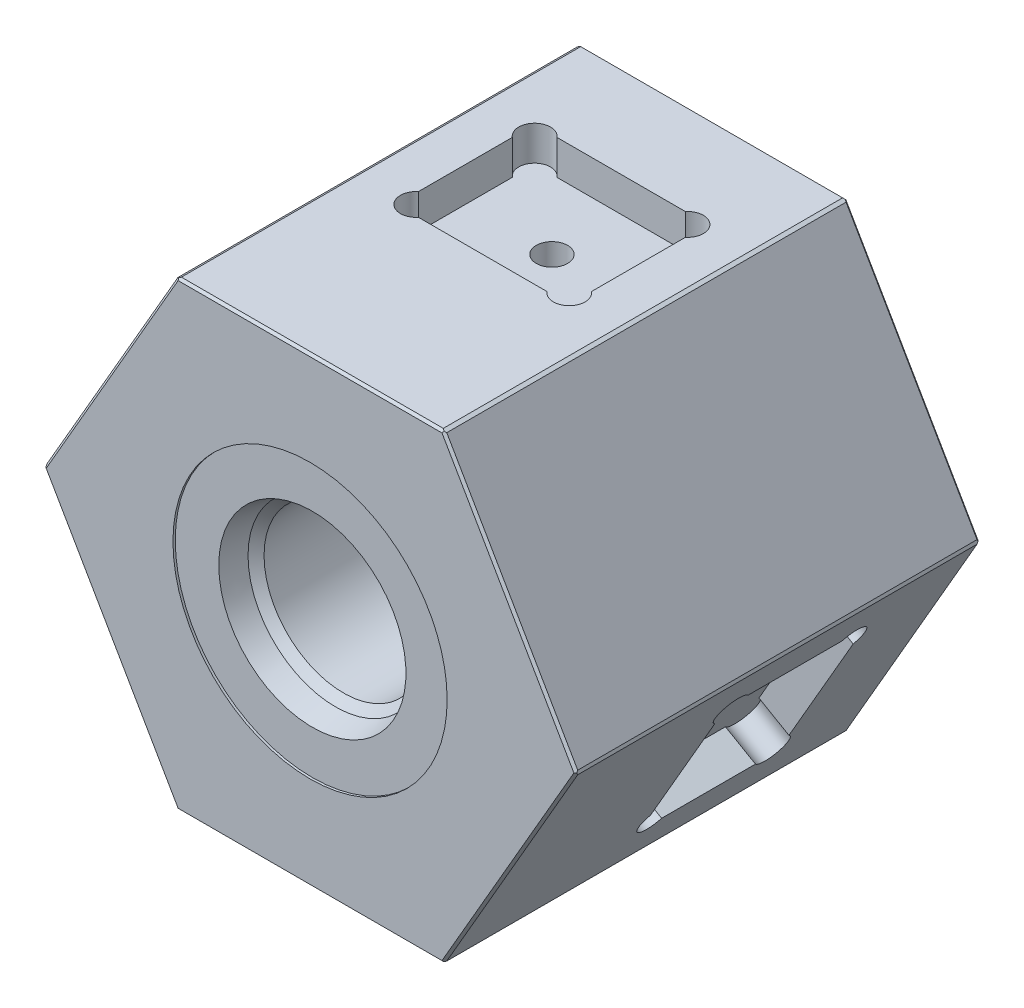
SolidWorks part; units mm, degrees
material "6061-T6 (SS)"
ref_plane "Front" through (0, 0, 0) normal (0, 0, 1) x (1, 0, 0)
ref_plane "Top" through (0, 0, 0) normal (0, 1, 0) x (1, 0, 0)
ref_plane "Right" through (0, 0, 0) normal (1, 0, 0) x (0, 0, -1)
sketch "Sketch1" plane through (0, 0, 0) normal (0, 0, 1) x (1, 0, 0)
  line L1 (29.3294, 0) -> (14.6647, 25.4)
  line L2 (14.6647, 25.4) -> (-14.6647, 25.4)
  line L3 (-14.6647, 25.4) -> (-29.3294, 0)
  line L4 (-29.3294, 0) -> (-14.6647, -25.4)
  line L5 (-14.6647, -25.4) -> (14.6647, -25.4)
  line L6 (14.6647, -25.4) -> (29.3294, 0)
  circle A0 centre (0, 0) radius 25.4 construction
  circle A1 centre (0, 0) radius 8.255
  dimension "D1" = 50.8
  dimension "D2" = 16.51
extrude "Boss-Extrude1" add sketch "Sketch1" along normal blind 44.45
sketch "Sketch2" plane through (0, 0, 44.45) normal (0, 0, 1) x (1, 0, 0)
  point P0 (0, 0)
ref_plane "Plane1" through (0, 0, 0) normal (0.866, 0.5, 0) x (0, 0, -1)
sketch "Sketch14" plane through (0, 25.4, 0) normal (0, 1, 0) x (1, 0, 0)
  line L0 (14.6647, 0) -> (-14.6647, -44.45) construction
  line L4 (14.6647, 0) -> (-14.6647, 0)
  line L5 (-14.6647, 0) -> (-14.6647, -44.45)
  line L6 (-14.6647, -44.45) -> (14.6647, -44.45)
  line L7 (14.6647, -44.45) -> (14.6647, 0)
  line L8 (14.6647, 0) -> (-14.6647, 0) construction
  line L9 (-14.6647, 0) -> (-14.6647, -44.45) construction
  line L10 (-14.6647, -44.45) -> (14.6647, -44.45) construction
  line L11 (14.6647, -44.45) -> (14.6647, 0) construction
  circle A0 centre (0, -22.225) radius 2.4638
  dimension "D1" = 0
sketch "Sketch21" plane through (0, 0, 44.45) normal (0, 0, 1) x (1, 0, 0)
  line L0 (-29.3294, 0) -> (-24.2494, 0) construction
  line L1 (-24.2494, 8.7988) -> (-24.2494, -8.7988)
  line L3 (-24.2494, -8.7988) -> (-41.847, -8.7988)
  line L4 (-24.2494, -8.7988) -> (-24.2494, 8.7988)
  line L5 (-24.2494, 8.7988) -> (-41.847, 8.7988)
  line L6 (14.6647, -25.4) -> (29.3294, 0)
  line L7 (29.3294, 0) -> (14.6647, 25.4)
  line L8 (14.6647, 25.4) -> (-14.6647, 25.4)
  line L9 (-14.6647, 25.4) -> (-29.3294, 0)
  line L10 (-29.3294, 0) -> (-14.6647, -25.4)
  line L11 (-14.6647, -25.4) -> (14.6647, -25.4)
  line L12 (14.6647, -25.4) -> (29.3294, 0) construction
  line L13 (29.3294, 0) -> (14.6647, 25.4) construction
  line L14 (14.6647, 25.4) -> (-14.6647, 25.4) construction
  line L15 (-14.6647, 25.4) -> (-29.3294, 0) construction
  line L16 (-29.3294, 0) -> (-14.6647, -25.4) construction
  line L17 (-14.6647, -25.4) -> (14.6647, -25.4) construction
  line L18 (-41.847, -8.7988) -> (-41.847, 8.7988)
  point P10 (-24.2494, 0)
  dimension "D2" = 5.08
  dimension "D1" = 0
sketch "Sketch22" plane through (0, 0, 0) normal (0, 0, -1) x (-1, 0, 0)
  circle A0 centre (0, 0) radius 6.9977
  circle A1 centre (0, 0) radius 9.2075
  circle A2 centre (0, 0) radius 10.9728
  dimension "D1" = 13.9954
  dimension "D2" = 18.415
  dimension "D3" = 21.9456
sketch "Sketch23" plane through (0, 0, 0) normal (0, 0, -1) x (-1, 0, 0)
  line L0 (0, 0) -> (0, 12.192) construction
  point P4 (0, 12.192)
sketch "Sketch48" plane through (0, 0, 0) normal (0, 0, -1) x (-1, 0, 0)
  line L0 (15.875, 0) -> (13.0175, 0) construction
  circle A0 centre (0, 0) radius 13.0175
  circle A1 centre (0, 0) radius 18.7325
  dimension "D1" = 26.035
  dimension "D3" = 37.465
  dimension "D2" = 2.8575
sketch "Sketch32" plane through (-21.997, -12.7, 0) normal (-0.866, -0.5, 0) x (0, 0, 1)
  line L0 (0, 14.6647) -> (44.45, -14.6647) construction
  line L2 (8.0518, -6.35) -> (36.3982, -6.35)
  line L3 (8.0518, -6.35) -> (8.0518, 6.35)
  line L4 (0, 14.6647) -> (0, -14.6647)
  line L5 (0, -14.6647) -> (44.45, -14.6647)
  line L6 (44.45, -14.6647) -> (44.45, 14.6647)
  line L7 (44.45, 14.6647) -> (0, 14.6647)
  line L8 (0, 14.6647) -> (0, -14.6647) construction
  line L9 (0, -14.6647) -> (44.45, -14.6647) construction
  line L10 (44.45, -14.6647) -> (44.45, 14.6647) construction
  line L11 (44.45, 14.6647) -> (0, 14.6647) construction
  line L12 (8.0518, 6.35) -> (36.3982, 6.35)
  line L13 (36.3982, -6.35) -> (36.3982, 6.35)
  line L14 (8.0518, -6.35) -> (36.3982, 6.35) construction
  line L15 (8.0518, 6.35) -> (36.3982, -6.35) construction
  point P2 (22.225, 0)
  point P4 (22.225, 0)
  dimension "D1" = 0
extrude "Cut-Extrude12" [suppressed] cut sketch "Sketch32" against normal blind 7.62
sketch "Sketch33" [suppressed] plane through (-21.997, -12.7, 0) normal (-0.866, -0.5, 0) x (0, 0, 1)
  line L0 (8.0518, 6.35) -> (8.2763, 6.1255) construction
  line L1 (22.225, 6.35) -> (22.225, 3.261) construction
  line L2 (8.0518, 0) -> (11.2132, 0) construction
  line L4 (0, 14.6647) -> (0, -14.6647)
  line L5 (0, -14.6647) -> (44.45, -14.6647)
  line L6 (44.45, -14.6647) -> (44.45, 14.6647)
  line L7 (44.45, 14.6647) -> (0, 14.6647)
  line L8 (0, 14.6647) -> (0, -14.6647) construction
  line L9 (0, -14.6647) -> (44.45, -14.6647) construction
  line L10 (44.45, -14.6647) -> (44.45, 14.6647) construction
  line L11 (44.45, 14.6647) -> (0, 14.6647) construction
  line L12 (36.3982, -6.35) -> (36.3982, 6.35)
  line L13 (36.3982, 6.35) -> (8.0518, 6.35)
  line L14 (8.0518, 6.35) -> (8.0518, -6.35)
  line L15 (8.0518, -6.35) -> (36.3982, -6.35)
  line L16 (36.3982, -6.35) -> (36.3982, 6.35) construction
  line L17 (36.3982, 6.35) -> (8.0518, 6.35) construction
  line L18 (8.0518, 6.35) -> (8.0518, -6.35) construction
  line L19 (8.0518, -6.35) -> (36.3982, -6.35) construction
  circle A0 centre (8.2763, 6.1255) radius 1.5875
  circle A1 centre (8.2763, -6.1255) radius 1.5875
  circle A2 centre (36.1737, -6.1255) radius 1.5875
  circle A3 centre (36.1737, 6.1255) radius 1.5875
  dimension "D3" = 3.175
  dimension "D4" = 0.3175
extrude "Cut-Extrude13" [suppressed] cut sketch "Sketch33" against normal blind 7.62
pattern_circular "CirPattern2" [suppressed] count 3 over 360
chamfer "Chamfer1" distance 0.254 angle 45 6 edges at (0, -25.4, 44.45) (-21.997, -12.7, 44.45) (-21.997, 12.7, 44.45) (0, 25.4, 44.45) (21.997, -12.7, 44.45) (21.997, 12.7, 44.45)
chamfer "Chamfer2" distance 0.254 angle 45 6 edges at (0, 25.4, 0) (-21.997, 12.7, 0) (-21.997, -12.7, 0) (0, -25.4, 0) (21.997, -12.7, 0) (21.997, 12.7, 0)
sketch "Sketch31" plane through (0, 0, 0) normal (0, 0, -1) x (-1, 0, 0)
  line L0 (24.2494, 8.7988) -> (24.2494, -8.7988) construction
  line L1 (24.2494, -8.7988) -> (41.847, -8.7988) construction
  line L2 (41.847, -8.7988) -> (41.847, 8.7988) construction
  line L3 (24.2494, 8.7988) -> (41.847, 8.7988) construction
  line L4 (24.2494, -8.7988) -> (24.2494, 8.7988) construction
  line L5 (24.2494, 8.7988) -> (24.2494, -8.7988) construction
  line L6 (24.2494, -8.7988) -> (41.847, -8.7988)
  line L7 (41.847, -8.7988) -> (41.847, 8.7988)
  line L8 (24.2494, 8.7988) -> (41.847, 8.7988)
  line L9 (24.2494, -8.7988) -> (24.2494, 8.7988)
sketch "Sketch26" plane through (-21.997, 12.7, 0) normal (-0.866, 0.5, 0) x (0, 0, 1)
  line L0 (0, 14.6647) -> (44.45, -1.9647) construction
  line L2 (8.0518, 0) -> (36.3982, 0)
  line L3 (8.0518, 0) -> (8.0518, 12.7)
  line L4 (0.254, 14.6647) -> (0.254, -14.6647)
  line L12 (8.0518, 12.7) -> (36.3982, 12.7)
  line L13 (36.3982, 0) -> (36.3982, 12.7)
  line L14 (8.0518, 0) -> (36.3982, 12.7) construction
  line L15 (8.0518, 12.7) -> (36.3982, 0) construction
  line L18 (44.196, 14.6647) -> (0.254, 14.6647)
  line L19 (44.196, 14.6647) -> (0.254, 14.6647)
  line L20 (0.254, -14.6647) -> (44.196, -14.6647)
  line L21 (0.254, -14.6647) -> (44.196, -14.6647)
  line L30 (44.196, -14.6647) -> (44.196, 14.6647)
  line L33 (0.254, 14.6647) -> (0.254, -14.6647)
  line L34 (44.196, -14.6647) -> (44.196, 14.6647)
  point P2 (22.225, 6.35)
  point P4 (22.225, 6.35)
  dimension "D2" = 28.3464
  dimension "D3" = 12.7
  dimension "D1" = 0
sketch "Sketch41" plane through (21.997, 12.7, 0) normal (0.866, 0.5, 0) x (0, 0, -1)
  line L0 (-44.196, 14.6647) -> (-0.254, -14.6647) construction
  line L2 (-27.305, 11.176) -> (-17.145, 11.176)
  line L3 (-31.115, 7.366) -> (-31.115, -7.366)
  line L4 (-0.254, -14.6647) -> (-0.254, 14.6647)
  line L5 (-44.196, -14.6647) -> (-0.254, -14.6647)
  line L7 (-44.196, -14.6647) -> (-0.254, -14.6647)
  line L12 (-27.305, -11.176) -> (-17.145, -11.176)
  line L13 (-13.335, 7.366) -> (-13.335, -7.366)
  line L14 (-31.115, 11.176) -> (-13.335, -11.176) construction
  line L15 (-31.115, -11.176) -> (-13.335, 11.176) construction
  line L19 (-0.254, 14.6647) -> (-44.196, 14.6647)
  line L20 (-0.254, 14.6647) -> (-44.196, 14.6647)
  line L23 (-44.196, 14.6647) -> (-44.196, -14.6647)
  line L27 (-0.254, -14.6647) -> (-0.254, 14.6647)
  line L28 (-44.196, 14.6647) -> (-44.196, -14.6647)
  arc A0 (-27.305, -11.176) -> (-31.115, -7.366) centre (-27.305, -7.366) cw
  arc A1 (-13.335, -7.366) -> (-17.145, -11.176) centre (-17.145, -7.366) cw
  arc A2 (-17.145, 11.176) -> (-13.335, 7.366) centre (-17.145, 7.366) cw
  arc A3 (-27.305, 11.176) -> (-31.115, 7.366) centre (-27.305, 7.366) ccw
  point P2 (-22.225, 0)
  dimension "D2" = 3.81
  dimension "D1" = 0
sketch "Sketch42" plane through (0, 25.4, 0) normal (0, 1, 0) x (1, 0, 0)
  line L0 (-14.6647, -0.254) -> (14.6647, -44.196) construction
  line L1 (-14.6647, -44.196) -> (14.6647, -0.254) construction
  line L2 (-7.62, -10.2108) -> (7.62, -10.2108)
  line L3 (-9.525, -12.1158) -> (-9.525, -23.5458)
  line L4 (14.6647, -0.254) -> (-14.6647, -0.254)
  line L5 (14.6647, -44.196) -> (14.6647, -0.254)
  line L7 (14.6647, -44.196) -> (14.6647, -0.254)
  line L12 (-7.62, -25.4508) -> (7.62, -25.4508)
  line L13 (9.525, -12.1158) -> (9.525, -23.5458)
  line L14 (-9.525, -10.2108) -> (9.525, -25.4508) construction
  line L15 (-9.525, -25.4508) -> (9.525, -10.2108) construction
  line L16 (0, -22.225) -> (0, -17.8308) construction
  line L19 (-14.6647, -0.254) -> (-14.6647, -44.196)
  line L20 (-14.6647, -0.254) -> (-14.6647, -44.196)
  line L23 (-14.6647, -44.196) -> (14.6647, -44.196)
  line L27 (14.6647, -0.254) -> (-14.6647, -0.254)
  line L28 (-14.6647, -44.196) -> (14.6647, -44.196)
  arc A0 (-7.62, -25.4508) -> (-9.525, -23.5458) centre (-7.62, -23.5458) cw
  arc A1 (9.525, -23.5458) -> (7.62, -25.4508) centre (7.62, -23.5458) cw
  arc A2 (7.62, -10.2108) -> (9.525, -12.1158) centre (7.62, -12.1158) cw
  arc A3 (-7.62, -10.2108) -> (-9.525, -12.1158) centre (-7.62, -12.1158) ccw
  point P2 (0, -17.8308)
  dimension "D2" = 1.905
  dimension "D3" = 15.24
  dimension "D4" = 19.05
  dimension "D5" = 43.942
  dimension "D6" = 17.5768
extrude "Cut-Extrude16" cut sketch "Sketch42" against normal blind 3.81 contours A3 L2 A2 L13 A1 L12 A0 L3
sketch "Sketch43" plane through (0, 0, 0) normal (0, 1, 0) x (1, 0, 0)
  line L0 (0, -44.45) -> (0, -50044.45) construction
  line L1 (-8.255, -44.45) -> (8.255, -44.45) construction
  line L3 (14.518, -44.45) -> (-14.518, -44.45) construction
  line L4 (10.2997, -44.196) -> (10.2997, -41.656) construction
  line L5 (10.2997, -44.196) -> (9.6191, -41.656)
  line L6 (10.2997, -41.656) -> (11.3639, -41.656) construction
  line L7 (0, -50.7062) -> (8.7376, -50.7062) construction
  line L8 (9.6191, -41.656) -> (8.7376, -40.7745)
  line L9 (8.7376, -50.7062) -> (8.7376, -51.9414) construction
  line L10 (8.7376, -40.7745) -> (8.7376, -23.2993)
  line L13 (8.7376, -23.2993) -> (4.9657, -21.1216)
  line L14 (0, -59.4121) -> (4.9657, -59.4121) construction
  line L15 (4.9657, -59.4121) -> (4.9657, 16.661) construction
  line L16 (4.9657, -21.1216) -> (0, -21.1216)
  line L19 (10.2997, -44.196) -> (15.0876, -44.196)
  line L20 (0, -44.45) -> (0, -21.1216)
  line L21 (15.0876, -44.196) -> (15.0876, -44.45)
  line L22 (15.0876, -44.45) -> (0, -44.45)
  line L24 (14.518, -44.45) -> (-14.518, -44.45) construction
  point P4 (0, -44.45)
  dimension "D1" = 15
  dimension "D2" = 0.8815
  dimension "D3" = 2.54
  dimension "D4" = 45
  dimension "D5" = 8.7376
  dimension "D6" = 4.9657
  dimension "D7" = 60
  dimension "D8" = 17.4752
  dimension "D9" = 0.254
  dimension "D10" = 15.0876
  dimension "D11" = 4.9657
  dimension "D12" = 23.3284
revolve "Cut-Revolve1" cut sketch "Sketch43" angle 360 about L0
pattern_circular "CirPattern3" count 3 over 360 about axis through (0, 0, 0) along (0, 0, 1) of "Cut-Extrude16"
ref_plane "YEAH BOIIIII" through (0, 0, 12.7) normal (0, 0, 1) x (1, 0, 0)
sketch "Sketch44" plane through (0, 0, 12.7) normal (0, 0, 1) x (1, 0, 0)
  line L0 (-21.997, 12.7) -> (43279.2731, -24987.3) construction
  line L1 (-14.6647, 25.4) -> (-29.3294, 0) construction
  line L2 (-21.764, 12.5655) -> (-24.8565, 7.2092) construction
  line L3 (-24.8565, 7.2092) -> (-22.8108, 6.0281) construction
  line L4 (-24.8565, 7.2092) -> (-22.5597, 6.4629)
  line L5 (-9.465, 2.9423) -> (-2.8658, -0.8677)
  line L6 (-22.8108, 6.0281) -> (-23.9458, 4.0621) construction
  line L7 (-26.3057, 15.1876) -> (-28.7568, 10.9421) construction
  line L8 (-28.7568, 10.9421) -> (-27.2096, 10.0489) construction
  line L9 (-22.5597, 6.4629) -> (-21.4934, 6.7486)
  line L10 (-21.4934, 6.7486) -> (-12.1828, 1.3731)
  line L11 (-12.1828, 1.3731) -> (-9.465, 2.9423)
  line L12 (-23.5705, 13.6084) -> (-24.6627, 11.7167) construction
  line L13 (-24.6627, 11.7167) -> (-23.5031, 11.0472) construction
  line L14 (-2.8658, -0.8677) -> (-1.7736, 1.024)
  line L15 (-1.7736, 1.024) -> (-21.764, 12.5655)
  line L16 (-24.8565, 7.2092) -> (-27.0218, 3.4587)
  line L17 (-27.0218, 3.4587) -> (-27.2548, 3.5932)
  line L18 (-27.2548, 3.5932) -> (-21.997, 12.7)
  line L19 (-21.997, 12.7) -> (-21.764, 12.5655)
  line L20 (-14.6647, 25.4) -> (-29.3294, 0) construction
  line L21 (-14.6647, 25.4) -> (-29.3294, 0) construction
  point P4 (-21.997, 12.7)
  dimension "D1" = 6.1849
  dimension "D2" = 2.3622
  dimension "D3" = 12
  dimension "D4" = 4.9022
  dimension "D5" = 45
  dimension "D6" = 13.8938
  dimension "D7" = 60
  dimension "D8" = 2.1844
  dimension "D9" = 23.0829
  dimension "D10" = 10.5156
  dimension "D11" = 0.2691
  dimension "D12" = 2.1844
revolve "Cut-Revolve2" cut sketch "Sketch44" angle 360 about L15
pattern_circular "CirPattern4" count 2 over 120 about axis through (0, 0, 0) along (0, 0, 1) of "Cut-Revolve2"
sketch "Sketch45" plane through (-18.6975, -10.795, 0) normal (-0.866, -0.5, 0) x (0, 0, 1)
  line L0 (17.8308, -9.525) -> (17.8308, 9.525) construction
  line L1 (12.1158, -9.525) -> (23.5458, -9.525) construction
  line L2 (12.1158, 9.525) -> (23.5458, 9.525) construction
  line L3 (10.2108, 0) -> (25.4508, 0) construction
  line L4 (10.2108, -7.62) -> (10.2108, 7.62) construction
  line L5 (25.4508, -7.62) -> (25.4508, 7.62) construction
  point P12 (17.8308, 0)
hole_wizard "#8-32 Tapped Hole1" positions "Sketch46" profile "Sketch47" tap size "#8-32" standard "ANSI Inch"
sketch "Sketch46" plane through (-18.6975, -10.795, 0) normal (-0.866, -0.5, 0) x (0, 0, 1)
  point P0 (17.8308, 0)
sketch "Sketch47" plane through (-18.6975, -10.795, 17.8308) normal (0, 0, 1) x (0.5, -0.866, 0)
  line L0 (0, 0) -> (0, 11.1978)
  line L1 (0, 11.1978) -> (1.7272, 10.16)
  line L2 (1.7272, 10.16) -> (1.7272, 0)
  line L5 (1.7272, 0) -> (0, 0)
  line L10 (0, 11.1978) -> (-1.7272, 10.16) construction
  line L11 (0, -6.35) -> (0, 107.95) construction
  dimension "Tap Drill Dia." = 3.4544
  dimension "Tap Drill Depth" = 10.16
  dimension "Drill Angle" = 118
cosmetic thread "Hole Thread2" parameters "D1"=9.398, "D2"=4.1656
pattern_circular "CirPattern5" count 3 over 360 about axis through (0, 0, 0) along (0, 0, 1) of "#8-32 Tapped Hole1"
sketch "Sketch49" plane through (0, 0, 0) normal (1, 0, 0) x (0, 0, -1)
  line L0 (0, 0) -> (50000, 0) construction
  line L1 (0, 0) -> (0, 23.622)
  line L2 (0, 0) -> (0, 25.146) construction
  line L3 (0, 23.622) -> (0.381, 23.622)
  line L4 (0.381, 23.622) -> (0.381, 15.8432)
  line L5 (0.381, 15.8432) -> (2.667, 15.8432)
  line L6 (2.667, 15.8432) -> (2.667, 14.605)
  line L7 (2.667, 14.605) -> (5.842, 14.605)
  line L8 (0, -8.255) -> (0, 8.255) construction
  line L9 (0, -8.255) -> (0, 8.255) construction
  line L10 (0, 8.255) -> (-2.4758, 8.255) construction
  line L11 (5.842, 14.605) -> (5.842, 12.7508)
  line L12 (5.842, 8.255) -> (0, 8.255)
  line L13 (0, 8.255) -> (0, 23.622)
  line L14 (14.8885, 0) -> (14.8885, 12.7508) construction
  line L15 (5.842, 12.7508) -> (4.5466, 12.7508)
  line L16 (4.5466, 12.7508) -> (4.5466, 10.6172)
  line L17 (4.5466, 10.6172) -> (5.842, 10.6172)
  line L18 (5.842, 10.6172) -> (5.842, 8.255)
  dimension "D1" = 23.622
  dimension "D2" = 15.8432
  dimension "D3" = 14.605
  dimension "D4" = 3.175
  dimension "D5" = 2.286
  dimension "D6" = 12.7508
  dimension "D7" = 1.2954
  dimension "D8" = 2.1336
  dimension "D9" = 0.381
  dimension "D10" = 5.461
revolve "Revolve1" add sketch "Sketch49" angle 360 about L0
hole_wizard "#6-32 Tapped Hole1" positions "Sketch24" profile "Sketch25" tap size "#6-32" standard "ANSI Inch"
sketch "Sketch24" plane through (0, 0, -0.381) normal (0, 0, -1) x (-1, 0, 0)
  line L0 (0, 0) -> (20.32, 0) construction
  line L1 (0, 0) -> (24.8294, -14.3353) construction
  line L11 (14.518, -25.146) -> (14.6647, -25.4)
  line L12 (14.6647, -25.4) -> (29.3294, 0)
  line L13 (29.3294, 0) -> (29.0361, 0)
  line L14 (29.0361, 0) -> (14.518, -25.146)
  line L15 (14.518, -25.146) -> (14.6647, -25.4)
  line L16 (14.6647, -25.4) -> (29.3294, 0)
  line L17 (29.3294, 0) -> (29.0361, 0)
  line L18 (29.0361, 0) -> (14.518, -25.146) construction
  point P11 (20.32, 0)
  dimension "D1" = 20.32
  dimension "D2" = 0
  dimension "D3" = 30
sketch "Sketch25" plane through (-20.32, 0, -0.381) normal (1, 0, 0) x (0, 1, 0)
  line L0 (0, 0) -> (0, 7.1627)
  line L1 (0, 7.1627) -> (1.3525, 6.35)
  line L2 (1.3525, 6.35) -> (1.3525, 0)
  line L5 (1.3525, 0) -> (0, 0)
  line L10 (0, 7.1627) -> (-1.3526, 6.35) construction
  line L11 (0, -6.35) -> (0, 107.95) construction
  dimension "Tap Drill Dia." = 2.7051
  dimension "Tap Drill Depth" = 6.35
  dimension "Drill Angle" = 118
cosmetic thread "Hole Thread11" parameters "D1"=5.588, "D2"=3.5052
pattern_circular "CirPattern6" count 2 over 60 about axis through (0, 0, -5.842) along (0, 0, 1) of "#6-32 Tapped Hole1"
pattern_circular "CirPattern7" count 2 over 360 about axis through (0, 0, 0) along (0, 0, 1) of "CirPattern6", "#6-32 Tapped Hole1"
sketch "Sketch51" plane through (0, 0, -0.381) normal (0, 0, -1) x (-1, 0, 0)
  line L0 (0, 0) -> (25.1717, -14.5329) construction
  line L1 (14.518, -25.146) -> (29.0361, 0) construction
  line L2 (14.518, -25.146) -> (29.0361, 0) construction
  line L3 (0, 0) -> (-3.5285, -20.0113) construction
  line L4 (0, 0) -> (-15.566, -13.0614) construction
  line L5 (0, 0) -> (10.16, -17.5976) construction
  line L6 (0, 0) -> (3.5285, 20.0113) construction
  line L7 (0, 0) -> (15.566, 13.0614) construction
  line L8 (0, 0) -> (20.32, 0) construction
  dimension "D3" = 20.32
  dimension "D4" = 20.32
  dimension "D5" = 30
  dimension "D1" = 40
  dimension "D2" = 40
  dimension "D6" = 30
hole_wizard "#6-32 Tapped Hole2" positions "Sketch56" profile "Sketch57" tap size "#6-32" standard "ANSI Inch"
sketch "Sketch56" plane through (0, 0, -0.381) normal (0, 0, -1) x (-1, 0, 0)
  point P0 (15.566, 13.0614)
  point P3 (3.5285, 20.0113)
  point P6 (-15.566, -13.0614)
  point P9 (-3.5285, -20.0113)
sketch "Sketch57" plane through (-15.566, 13.0614, -0.381) normal (1, 0, 0) x (0, 1, 0)
  line L0 (0, 0) -> (0, 7.1627)
  line L1 (0, 7.1627) -> (1.3525, 6.35)
  line L2 (1.3525, 6.35) -> (1.3525, 0)
  line L5 (1.3525, 0) -> (0, 0)
  line L10 (0, 7.1627) -> (-1.3526, 6.35) construction
  line L11 (0, -6.35) -> (0, 107.95) construction
  dimension "Tap Drill Dia." = 2.7051
  dimension "Tap Drill Depth" = 6.35
  dimension "Drill Angle" = 118
cosmetic thread "Hole Thread6" parameters "D1"=5.588, "D2"=3.5052
cosmetic thread "Hole Thread7" parameters "D1"=5.588, "D2"=3.5052
cosmetic thread "Hole Thread8" parameters "D1"=5.588, "D2"=3.5052
cosmetic thread "Hole Thread9" parameters "D1"=5.588, "D2"=3.5052
sketch "Sketch50" plane through (0, 0, -0.381) normal (0, 0, -1) x (-1, 0, 0)
  line L0 (16.8026, -11.537) -> (18.3927, -8.783) construction
  line L2 (0, 0) -> (17.5976, -10.16) construction
  line L3 (17.5976, -10.16) -> (17.2039, -10.8419) construction
  line L4 (17.5976, -10.16) -> (17.9913, -9.4781) construction
  line L5 (17.2039, -10.8419) -> (17.9913, -9.4781) construction
  line L6 (16.5088, -10.4406) -> (17.2962, -9.0768)
  line L7 (17.899, -11.2432) -> (18.6864, -9.8794)
  line L8 (0, 0) -> (-17.5976, 10.16) construction
  line L9 (0, 0) -> (17.5976, -10.16) construction
  line L10 (0, 0) -> (25.1717, -14.5329) construction
  line L11 (0, 0) -> (-14.6647, -25.4) construction
  circle A0 centre (0, 0) radius 20.32 construction
  arc A1 (16.5088, -10.4406) -> (17.899, -11.2432) centre (17.2039, -10.8419) ccw
  arc A2 (18.6864, -9.8794) -> (17.2962, -9.0768) centre (17.9913, -9.4781) ccw
  point P5 (17.5976, -10.16)
  point P9 (17.5976, -10.16)
  point P16 (0, 0)
  dimension "D5" = 0.8026
  dimension "D6" = 40.64
  dimension "D3" = 0.7874
  dimension "D4" = 0.7874
  dimension "D2" = 180
extrude "Boss-Extrude2" add sketch "Sketch50" along normal blind 1.27
sketch "Sketch58" plane through (0, 0, -5.842) normal (0, 0, -1) x (-1, 0, 0)
  circle A0 centre (0, 0) radius 10.6172 construction
  circle A1 centre (0, 0) radius 12.7508 construction
  circle A2 centre (0, 0) radius 10.6172
  circle A3 centre (0, 0) radius 12.7508
chamfer "Chamfer3" distance 0.254 angle 30 6 edges at (14.6647, -25.4, 22.225) (29.3294, 0, 22.225) (14.6647, 25.4, 22.225) (-14.6647, -25.4, 22.225) (-14.6647, 25.4, 22.225) (-29.3294, 0, 22.225)
sketch "Sketch60" plane through (0, 25.4, 0) normal (0, 1, 0) x (1, 0, 0)
  line L0 (-7.62, -10.2108) -> (-9.525, -10.2108) construction
  line L1 (-9.525, -10.2108) -> (-9.525, -12.1158) construction
  line L2 (-9.525, -10.2108) -> (-8.4137, -11.3221) construction
  line L4 (14.6647, -44.196) -> (14.6647, -0.254)
  line L5 (14.6647, -0.254) -> (-14.6647, -0.254)
  line L6 (-14.6647, -0.254) -> (-14.6647, -44.196)
  line L7 (-14.6647, -44.196) -> (14.6647, -44.196)
  line L8 (14.6647, -44.196) -> (14.6647, -0.254)
  line L9 (14.6647, -0.254) -> (-14.6647, -0.254)
  line L10 (-14.6647, -0.254) -> (-14.6647, -44.196)
  line L11 (-14.6647, -44.196) -> (14.6647, -44.196)
  line L12 (7.62, -10.2108) -> (-7.62, -10.2108)
  line L13 (9.525, -23.5458) -> (9.525, -12.1158)
  line L14 (-7.62, -25.4508) -> (7.62, -25.4508)
  line L15 (-9.525, -12.1158) -> (-9.525, -23.5458)
  line L16 (7.62, -10.2108) -> (-7.62, -10.2108) construction
  line L17 (9.525, -23.5458) -> (9.525, -12.1158) construction
  line L18 (-7.62, -25.4508) -> (7.62, -25.4508) construction
  line L19 (-9.525, -12.1158) -> (-9.525, -23.5458) construction
  circle A1 centre (-8.4137, -11.3221) radius 1.7462
  arc A4 (9.525, -12.1158) -> (7.62, -10.2108) centre (7.62, -12.1158) ccw
  arc A5 (7.62, -25.4508) -> (9.525, -23.5458) centre (7.62, -23.5458) ccw
  arc A6 (-9.525, -23.5458) -> (-7.62, -25.4508) centre (-7.62, -23.5458) ccw
  arc A7 (-7.62, -10.2108) -> (-9.525, -12.1158) centre (-7.62, -12.1158) ccw
  arc A8 (9.525, -12.1158) -> (7.62, -10.2108) centre (7.62, -12.1158) ccw construction
  arc A9 (7.62, -25.4508) -> (9.525, -23.5458) centre (7.62, -23.5458) ccw construction
  arc A10 (-9.525, -23.5458) -> (-7.62, -25.4508) centre (-7.62, -23.5458) ccw construction
  arc A11 (-7.62, -10.2108) -> (-9.525, -12.1158) centre (-7.62, -12.1158) ccw construction
  dimension "D4" = 3.4925
  dimension "D3" = 1.5716
extrude "Cut-Extrude17" cut sketch "Sketch60" against normal up to surface (3.81 mm away) contours A1 up to face at (0, 21.59, 19.558)
ref_plane "Plane2" through (0, 0, 0) normal (1, 0, 0) x (0, 0, -1)
ref_plane "Plane3" through (0, 0, 17.8308) normal (0, 0, 1) x (1, 0, 0)
mirror "Mirror1" about plane through (0, 0, 0) normal (1, 0, 0) of "Cut-Extrude17"
mirror "Mirror2" about plane through (0, 0, 17.8308) normal (0, 0, 1) of "Mirror1", "Cut-Extrude17"
sketch "Sketch61" plane through (-21.997, -12.7, 0) normal (-0.866, -0.5, 0) x (0, 0, 1)
  line L0 (25.4508, -7.62) -> (25.4508, 7.62) construction
  line L1 (12.1158, 9.525) -> (23.5458, 9.525) construction
  line L2 (25.4508, -7.62) -> (25.4508, 7.62) construction
  line L3 (12.1158, 9.525) -> (23.5458, 9.525) construction
  line L4 (23.5458, 9.525) -> (25.4508, 9.525) construction
  line L5 (25.4508, 9.525) -> (25.4508, 7.62) construction
  line L6 (25.4508, 9.525) -> (24.3395, 8.4137) construction
  circle A0 centre (24.3395, 8.4137) radius 1.7462
  dimension "D1" = 3.4925
  dimension "D2" = 1.5716
extrude "Cut-Extrude18" cut sketch "Sketch61" against normal up to surface (3.81 mm away) up to face at (-17.8339, -12.2908, 17.8308)
ref_plane "Plane4" through (0, 0, 17.8308) normal (0, 0, -1) x (-1, 0, 0)
ref_plane "Plane5" through (0, 0, 0) normal (0.5, -0.866, 0) x (-0.866, -0.5, 0)
mirror "Mirror3" about plane through (0, 0, 0) normal (0.5, -0.866, 0) of "Cut-Extrude18"
mirror "Mirror4" about plane through (0, 0, 17.8308) normal (0, 0, -1) of "Cut-Extrude18", "Mirror3"
ref_plane "Plane6" through (0, 0, 17.8308) normal (0, 0, -1) x (-1, 0, 0)
ref_plane "Plane7" through (0, 0, 0) normal (0.5, 0.866, 0) x (0.866, -0.5, 0)
sketch "Sketch62" plane through (21.997, -12.7, 0) normal (0.866, -0.5, 0) x (0, 0, -1)
  line L0 (-12.1158, -9.525) -> (-23.5458, -9.525) construction
  line L1 (-25.4508, 7.62) -> (-25.4508, -7.62) construction
  line L2 (-12.1158, -9.525) -> (-23.5458, -9.525) construction
  line L3 (-25.4508, 7.62) -> (-25.4508, -7.62) construction
  line L4 (-25.4508, -7.62) -> (-25.4508, -9.525) construction
  line L5 (-25.4508, -9.525) -> (-23.5458, -9.525) construction
  line L6 (-25.4508, -9.525) -> (-24.3395, -8.4137) construction
  circle A0 centre (-24.3395, -8.4137) radius 1.7462
  dimension "D2" = 3.4925
  dimension "D1" = 1.5716
extrude "Cut-Extrude19" cut sketch "Sketch62" against normal up to surface (3.81 mm away) contours A0 up to face at (19.5611, -9.2992, 17.8308)
mirror "Mirror5" about plane through (0, 0, 0) normal (0.5, 0.866, 0) of "Cut-Extrude19"
mirror "Mirror6" about plane through (0, 0, 17.8308) normal (0, 0, -1) of "Cut-Extrude19", "Mirror5"
equation "\"D4@Sketch33\"=0.1*\"D3@Sketch33\""
equation "\"D4@Sketch42\"=1.25*\"D3@Sketch42\""
equation "\"D3@Sketch48\"=\"D1@Sketch48\"+(4*\"D2@Sketch48\")"
equation "\"D6@Sketch42\"=\"D5@Sketch42\"*.4"
equation "\"D4@Sketch50\"=\"D3@Sketch50\""
equation "\"D4@Sketch51\"=\"D3@Sketch51\""
equation "\"D1@Sketch51\"=(180-(2*\"D5@Sketch51\"))/3"
equation "\"D2@Sketch51\"=\"D1@Sketch51\""
equation "\"D3@Sketch60\"=((\"D4@Sketch60\")/2)*.9"
equation "\"D2@Sketch61\"=0.9*(\"D1@Sketch61\")/2"
equation "\"D1@Sketch62\"=0.9*(\"D2@Sketch62\")/2"
